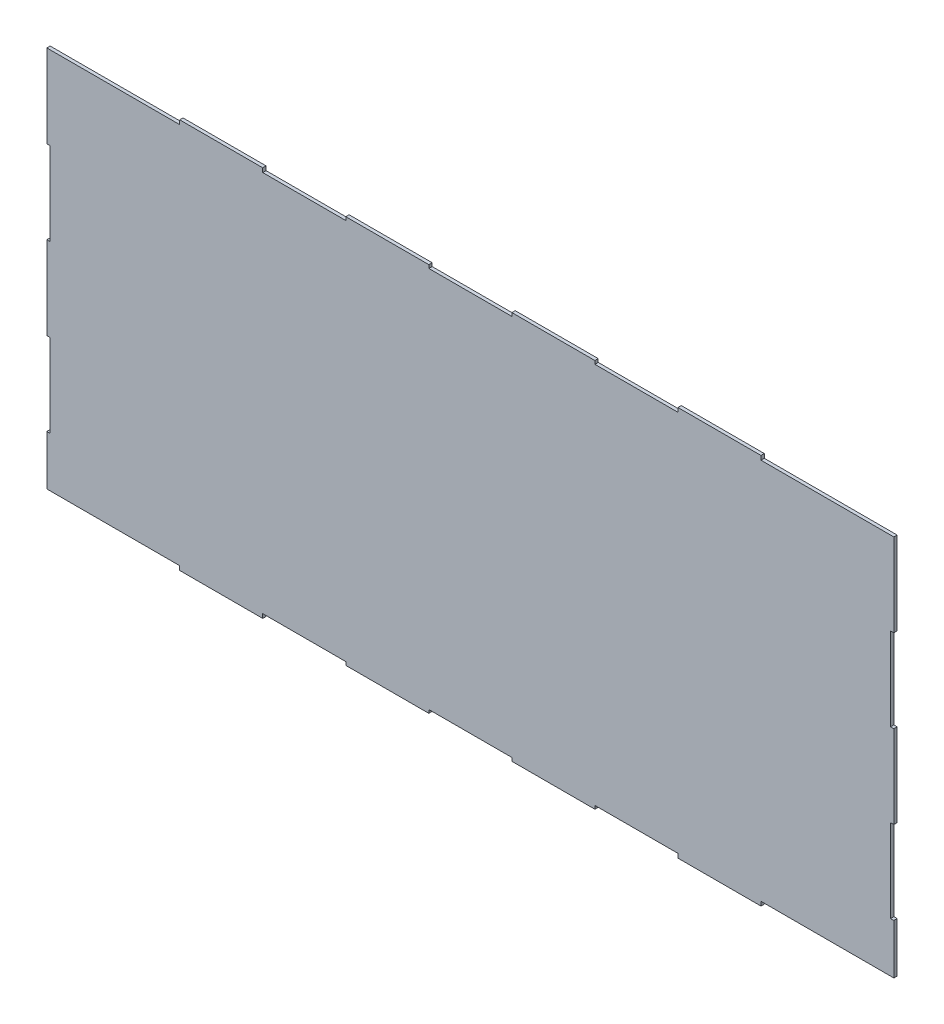
SolidWorks part; units mm, degrees
ref_plane "前视基准面" through (0, 0, 0) normal (0, 0, 1) x (1, 0, 0)
ref_plane "上视基准面" through (0, 0, 0) normal (0, 1, 0) x (1, 0, 0)
ref_plane "右视基准面" through (0, 0, 0) normal (1, 0, 0) x (0, 0, -1)
other "Configuration Table"
sketch "草图2" plane through (0, 0, 0) normal (0, 0, 1) x (1, 0, 0)
  line L0 (-510, 230) -> (-350, 230)
  line L1 (-250, 230) -> (-150, 230)
  line L2 (-50, 230) -> (50, 230)
  line L3 (150, 230) -> (250, 230)
  line L4 (350, 230) -> (510, 230)
  line L5 (510, -170) -> (510, -230)
  line L6 (510, -230) -> (350, -230)
  line L7 (250, -230) -> (150, -230)
  line L8 (50, -230) -> (-50, -230)
  line L9 (-150, -230) -> (-250, -230)
  line L10 (-350, -230) -> (-510, -230)
  line L11 (-510, -230) -> (-510, -170)
  line L12 (-510, -70) -> (-510, 30)
  line L13 (-510, 130) -> (-510, 230)
  line L18 (-510, 130) -> (-506, 130)
  line L19 (-506, 130) -> (-506, 30)
  line L20 (-506, 30) -> (-510, 30)
  line L22 (-510, -70) -> (-506, -70)
  line L23 (-506, -70) -> (-506, -170)
  line L24 (-506, -170) -> (-510, -170)
  line L25 (510, 130) -> (506, 130)
  line L26 (506, 130) -> (506, 30)
  line L27 (506, 30) -> (510, 30)
  line L28 (510, -70) -> (506, -70)
  line L29 (506, -70) -> (506, -170)
  line L30 (506, -170) -> (510, -170)
  line L31 (510, 230) -> (510, 130)
  line L32 (510, -70) -> (510, 30)
  line L34 (-50, -230) -> (-50, -234)
  line L35 (-50, -234) -> (-150, -234)
  line L36 (-150, -234) -> (-150, -230)
  line L38 (-250, -230) -> (-250, -235)
  line L39 (-250, -235) -> (-350, -235)
  line L40 (-350, -235) -> (-350, -230)
  line L41 (50, -230) -> (50, -234)
  line L42 (50, -234) -> (150, -234)
  line L43 (150, -234) -> (150, -230)
  line L44 (250, -230) -> (250, -235)
  line L45 (250, -235) -> (350, -235)
  line L46 (350, -235) -> (350, -230)
  line L62 (50, 230) -> (50, 234)
  line L63 (50, 234) -> (150, 234)
  line L64 (150, 234) -> (150, 230)
  line L65 (250, 230) -> (250, 235)
  line L66 (250, 235) -> (350, 235)
  line L67 (350, 235) -> (350, 230)
  line L68 (-50, 230) -> (-50, 234)
  line L69 (-50, 234) -> (-150, 234)
  line L70 (-150, 234) -> (-150, 230)
  line L71 (-250, 230) -> (-250, 235)
  line L72 (-250, 235) -> (-350, 235)
  line L73 (-350, 235) -> (-350, 230)
extrude "凸台-拉伸1" add sketch "草图2" along normal blind 4
